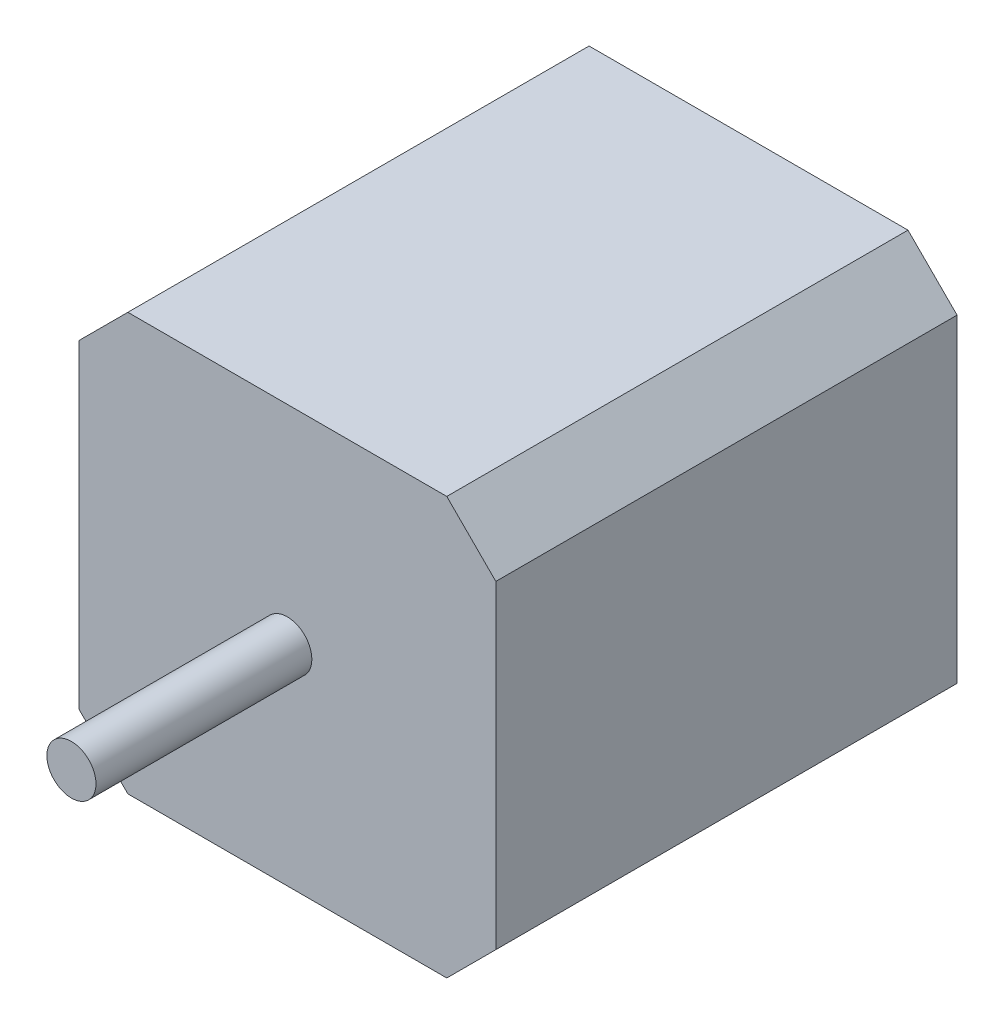
SolidWorks part; units mm, degrees
ref_plane "Front Plane" through (0, 0, 0) normal (0, 0, 1) x (1, 0, 0)
ref_plane "Top Plane" through (0, 0, 0) normal (0, 1, 0) x (1, 0, 0)
ref_plane "Right Plane" through (0, 0, 0) normal (1, 0, 0) x (0, 0, -1)
sketch "Sketch1" plane through (0, 0, 0) normal (0, 0, 1) x (1, 0, 0)
  line L1 (-41.6448, 27.598) -> (0.8552, 27.598)
  line L2 (-41.6448, 27.598) -> (-41.6448, -14.902)
  line L3 (-41.6448, -14.902) -> (0.8552, -14.902)
  line L4 (0.8552, 27.598) -> (0.8552, -14.902)
  dimension "D1" = 42.5
extrude "Boss-Extrude1" add sketch "Sketch1" along normal blind 47
chamfer "Chamfer1" distance 5 angle 45 4 edges at (0.8552, 27.598, 23.5) (0.8552, -14.902, 23.5) (-41.6448, -14.902, 23.5) (-41.6448, 27.598, 23.5)
sketch "Sketch2" plane through (0, 0, 47) normal (0, 0, 1) x (1, 0, 0)
  line L0 (-39.1448, 25.098) -> (-1.6448, -12.402) construction
  line L1 (-36.6448, 27.598) -> (-41.6448, 22.598) construction
  line L2 (-4.1448, -14.902) -> (0.8552, -9.902) construction
  circle A0 centre (-20.3948, 6.348) radius 2.5
extrude "Boss-Extrude2" add sketch "Sketch2" along normal blind 22
